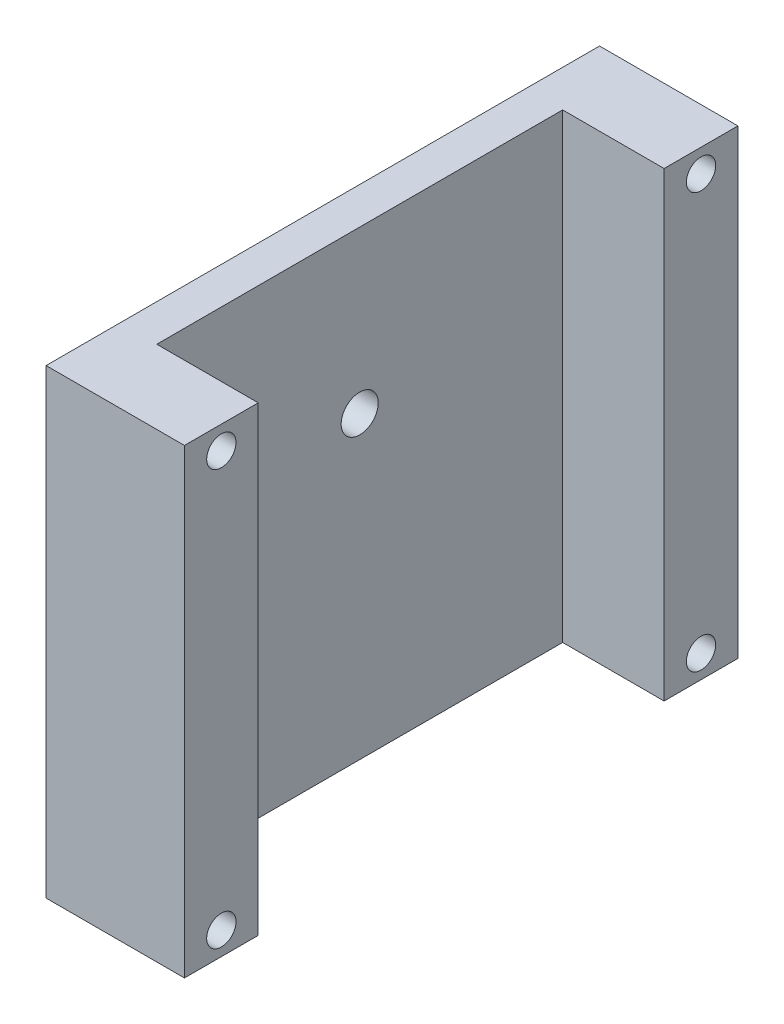
SolidWorks part; units mm, degrees
ref_plane "Front Plane" through (0, 0, 0) normal (0, 0, 1) x (1, 0, 0)
ref_plane "Top Plane" through (0, 0, 0) normal (0, 1, 0) x (1, 0, 0)
ref_plane "Right Plane" through (0, 0, 0) normal (1, 0, 0) x (0, 0, -1)
sketch "Sketch1" plane through (0, 0, 0) normal (1, 0, 0) x (0, 0, -1)
  line L1 (-38.1, -31.75) -> (38.1, -31.75)
  line L2 (-38.1, -31.75) -> (-38.1, 31.75)
  line L3 (-38.1, 31.75) -> (38.1, 31.75)
  line L4 (38.1, -31.75) -> (38.1, 31.75)
  line L5 (-38.1, -31.75) -> (38.1, 31.75) construction
  line L6 (-38.1, 31.75) -> (38.1, -31.75) construction
  point P0 (0, 0)
  dimension "D1" = 76.2
  dimension "D2" = 63.5
extrude "Boss-Extrude1" add sketch "Sketch1" along normal blind 19.05
sketch "Sketch2" plane through (19.05, 0, 0) normal (1, 0, 0) x (0, 0, -1)
  line L0 (38.1, 31.75) -> (-38.1, 31.75) construction
  line L1 (-27.94, -31.75) -> (27.94, -31.75)
  line L2 (-27.94, -31.75) -> (-27.94, 31.75)
  line L3 (-27.94, 31.75) -> (27.94, 31.75)
  line L4 (27.94, -31.75) -> (27.94, 31.75)
  line L5 (-27.94, -31.75) -> (27.94, 31.75) construction
  line L6 (-27.94, 31.75) -> (27.94, -31.75) construction
  line L7 (-38.1, 31.75) -> (-38.1, -31.75) construction
  point P0 (0, 0)
  dimension "D1" = 10.16
extrude "Cut-Extrude1" cut sketch "Sketch2" against normal blind 13.97
hole_wizard "#10-32 Tapped Hole1" positions "Sketch6" profile "Sketch5" tap size "#10-32" standard "ANSI Inch"
sketch "Sketch6" plane through (19.05, 0, 0) normal (1, 0, 0) x (0, 0, -1)
  line L0 (-27.94, 31.75) -> (-38.1, 31.75) construction
  point P0 (-33.02, 28.575)
  point P7 (-33.02, 31.75)
  dimension "D1" = 0
  dimension "D2" = 3.175
sketch "Sketch5" plane through (19.05, 28.575, 33.02) normal (0, 1, 0) x (0, 0, -1)
  line L0 (0, 0) -> (0, 14.9293)
  line L1 (0, 14.9293) -> (2.0193, 13.716)
  line L2 (2.0193, 13.716) -> (2.0193, 0)
  line L5 (2.0193, 0) -> (0, 0)
  line L10 (0, 14.9293) -> (-2.0193, 13.716) construction
  line L11 (0, -6.35) -> (0, 107.95) construction
  dimension "Tap Drill Dia." = 4.0386
  dimension "Tap Drill Depth" = 13.716
  dimension "Drill Angle" = 118
cosmetic thread "Hole Thread2" parameters "D1"=9.652, "D2"=4.826
hole_wizard "1/4-20 Tapped Hole1" positions "Sketch4" profile "Sketch3" tap size "1/4-20" standard "ANSI Inch"
sketch "Sketch4" plane through (5.08, 0, 0) normal (1, 0, 0) x (0, 0, -1)
  circle A0 centre (-33.02, 28.575) radius 2.0193 construction
  point P0 (0, 9.525)
  dimension "D1" = 0
  dimension "D2" = 19.05
sketch "Sketch3" plane through (5.08, 9.525, 0) normal (0, 1, 0) x (0, 0, -1)
  line L0 (0, 0) -> (0, 20.5838)
  line L1 (0, 20.5838) -> (2.5527, 19.05)
  line L2 (2.5527, 19.05) -> (2.5527, 0)
  line L5 (2.5527, 0) -> (0, 0)
  line L10 (0, 20.5838) -> (-2.5527, 19.05) construction
  line L11 (0, -6.35) -> (0, 107.95) construction
  dimension "Tap Drill Dia." = 5.1054
  dimension "Tap Drill Depth" = 19.05
  dimension "Drill Angle" = 118
cosmetic thread "Hole Thread1" parameters "D1"=5.08, "D2"=6.35
pattern_linear "LPattern1" count 2 spacing 57.15 along (0, -1, 0) count 2 spacing 66.04 along (0, 0, -1) of "#10-32 Tapped Hole1"
